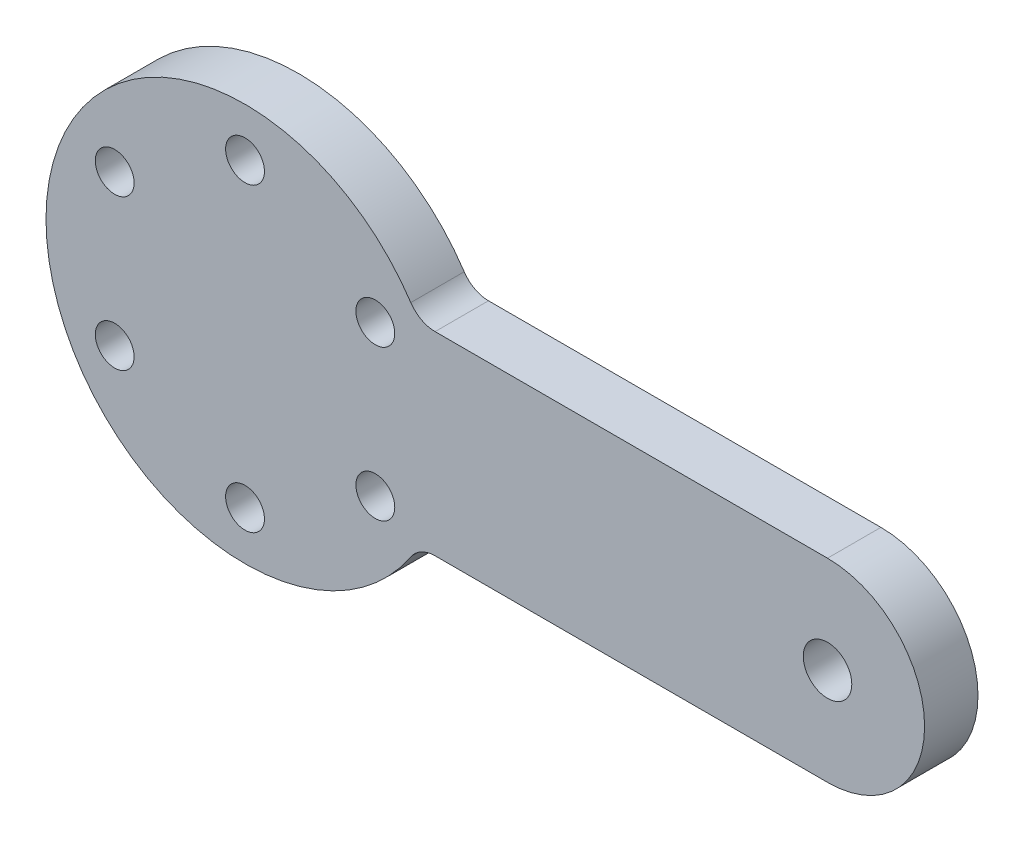
SolidWorks part; units mm, degrees
ref_plane "前基準面" through (0, 0, 0) normal (0, 0, 1) x (1, 0, 0)
ref_plane "上基準面" through (0, 0, 0) normal (0, 1, 0) x (1, 0, 0)
ref_plane "右基準面" through (0, 0, 0) normal (1, 0, 0) x (0, 0, -1)
sketch "草圖1" plane through (0, 0, 0) normal (0, 0, 1) x (1, 0, 0)
  line L0 (-80, 0) -> (-72.5, 0) construction
  line L1 (17.8955, 10) -> (60, 10)
  line L2 (17.8955, -10) -> (60, -10)
  line L3 (0, 0) -> (60, 0) construction
  arc A1 (60, -10) -> (60, 10) centre (60, 0) ccw
  circle A3 centre (60, 0) radius 2.5
  arc A6 (17.8955, 10) -> (17.8955, -10) centre (0, 0) ccw
  point P3 (0, 0)
  dimension "D1" = 10
  dimension "D3" = 5
  dimension "D4" = 41
  dimension "D2" = 60
extrude "填料-伸長1" add sketch "草圖1" along normal mid plane 5.5
sketch "草圖2" plane through (0, 0, 2.75) normal (0, 0, 1) x (1, 0, 0)
  circle A0 centre (0, 15.5) radius 2
  dimension "D1" = 4
  dimension "D2" = 15.5
extrude "除料-伸長1" cut sketch "草圖2" against normal up to next
pattern_circular "環狀複製排列1" count 6 over 360 about axis through (0, 0, 0) along (0, 0, 1) of "除料-伸長1"
fillet "圓角1" radius 3 2 edges at (17.8955, 10, 0) (17.8955, -10, 0)
